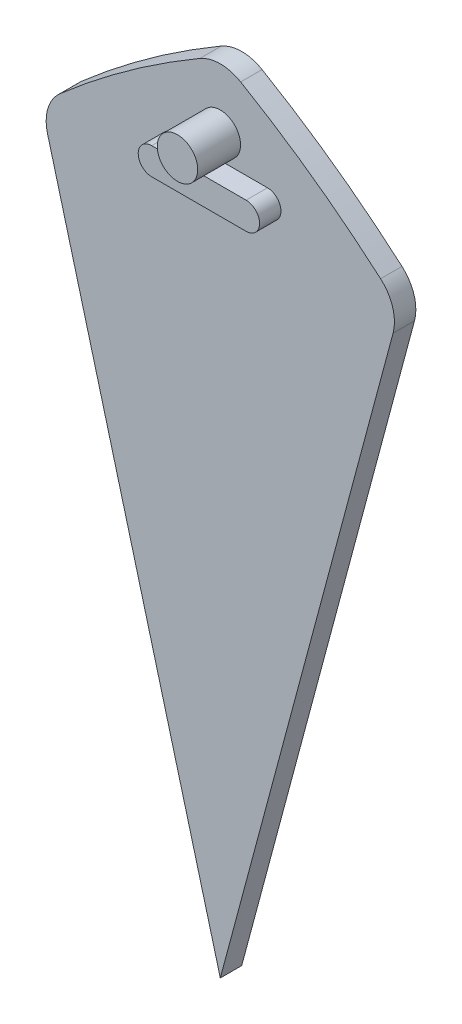
SolidWorks part; units mm, degrees
ref_plane "Front Plane" through (0, 0, 0) normal (0, 0, 1) x (1, 0, 0)
ref_plane "Top Plane" through (0, 0, 0) normal (0, 1, 0) x (1, 0, 0)
ref_plane "Right Plane" through (0, 0, 0) normal (1, 0, 0) x (0, 0, -1)
sketch "Sketch1" plane through (0, 0, 0) normal (0, 0, 1) x (1, 0, 0)
  line L0 (0, 0) -> (0, 187.7098) construction
  line L1 (0, 0) -> (-32.3524, 120.7407)
  line L2 (0, 0) -> (32.3524, 120.7407)
  circle A0 centre (0, 0) radius 125
  dimension "D1" = 250
  dimension "D2" = 15
  dimension "D3" = 15
extrude "Boss-Extrude1" add sketch "Sketch1" along normal blind 3.175 contours L1 L0 A0 | L0 L2 A0
sketch "Sketch2" plane through (0, 0, 3.175) normal (0, 0, 1) x (1, 0, 0)
  circle A0 centre (0, 0) radius 108.5 construction
  circle A1 centre (0, 108.5) radius 3
  dimension "D1" = 217
  dimension "D2" = 6
sketch "Sketch3" plane through (0, 0, 3.175) normal (0, 0, 1) x (1, 0, 0)
  line L0 (0, 0) -> (65, 0) construction
  line L1 (0, 0) -> (-65, 0) construction
  circle A0 centre (-65, 0) radius 135
  circle A1 centre (65, 0) radius 135
  line M4 (-32.3524, 120.7407) -> (0, 0)
  line M5 (0, 0) -> (32.3524, 120.7407)
  arc M6 (32.3524, 120.7407) -> (-32.3524, 120.7407) centre (0, 0) ccw
  dimension "D3" = 270
  dimension "D4" = 270
  dimension "D1" = 65
  dimension "D2" = 65
extrude "Cut-Extrude2" cut sketch "Sketch3" against normal blind 3.175 contours A1 A0 M6 M4 | A1 A0 M6 | A1 A0 M6 M5
fillet "Fillet1" radius 6 3 edges at (26.5777, 99.1893, 1.5875) (0, 118.3216, 1.5875) (-26.5777, 99.1893, 1.5875)
sketch "Sketch4" plane through (0, 0, 3.175) normal (0, 0, 1) x (1, 0, 0)
  line L0 (-45.1495, 103) -> (48.8964, 103) construction
  line L1 (0, 0) -> (0, 103) construction
  line L2 (7, 103) -> (-7, 103) construction
  line L3 (7, 101) -> (-7, 101)
  line L4 (7, 105) -> (-7, 105)
  arc A1 (7, 101) -> (7, 105) centre (7, 103) ccw
  arc A2 (-7, 105) -> (-7, 101) centre (-7, 103) ccw
  point P9 (0, 103)
  dimension "D1" = 103
  dimension "D2" = 14
  dimension "D3" = 4
extrude "Boss-Extrude2" add sketch "Sketch4" along normal blind 3.175
extrude "Boss-Extrude3" add sketch "Sketch2" along normal blind 6.35 contours A1
